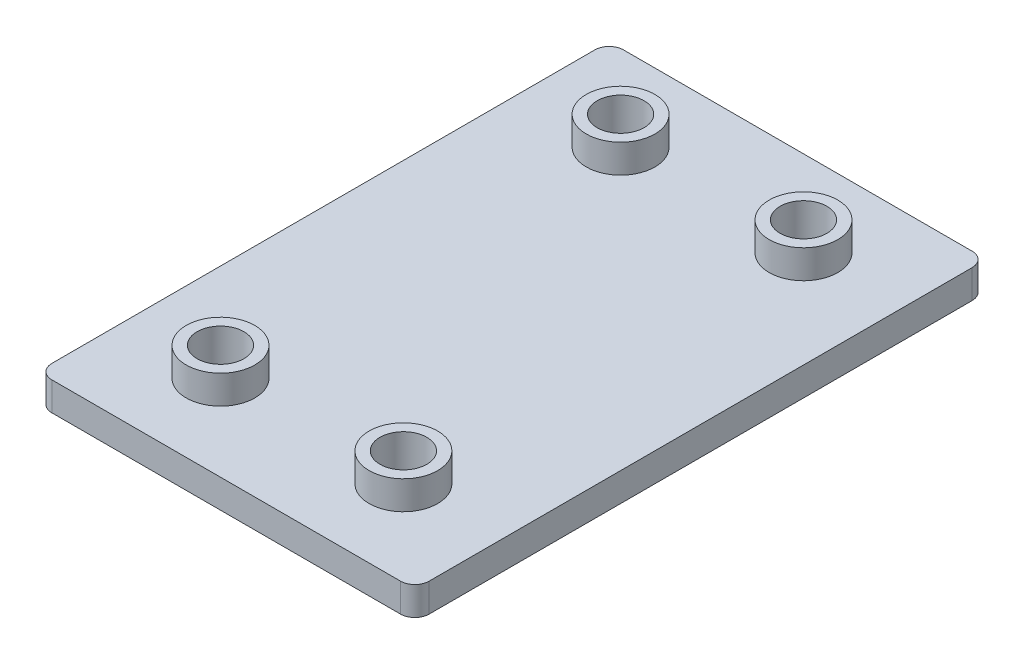
SolidWorks part; units mm, degrees
material "Custom Plastic"
ref_plane "Front Plane" through (0, 0, 0) normal (0, 0, 1) x (1, 0, 0)
ref_plane "Top Plane" through (0, 0, 0) normal (0, 1, 0) x (1, 0, 0)
ref_plane "Right Plane" through (0, 0, 0) normal (1, 0, 0) x (0, 0, -1)
sketch "Sketch1" plane through (0, 0, 0) normal (0, 1, 0) x (1, 0, 0)
  line L0 (0, 0) -> (0, -6.9405) construction
  line L1 (33, -50) -> (-33, -50)
  line L2 (33, -50) -> (33, 50)
  line L3 (33, 50) -> (-33, 50)
  line L4 (-33, -50) -> (-33, 50)
  line L5 (33, -50) -> (-33, 50) construction
  line L6 (33, 50) -> (-33, -50) construction
  line L7 (0, 0) -> (-7.7524, 0) construction
  point P0 (0, 0)
  dimension "D1" = 66
  dimension "D2" = 100
extrude "Boss-Extrude1" add sketch "Sketch1" along normal blind 5
sketch "Sketch2" plane through (0, 5, 0) normal (0, 1, 0) x (1, 0, 0)
  line L0 (0, 0) -> (0, -50000) construction
  line L1 (0, 0) -> (50000, 0) construction
  line L2 (33, 50) -> (-33, 50) construction
  circle A0 centre (-16, 35) radius 6
  circle A2 centre (16, 35) radius 6
  circle A3 centre (16, -35) radius 6
  circle A4 centre (-16, -35) radius 6
  dimension "D3" = 12
  dimension "D1" = 15
  dimension "D2" = 16
extrude "Boss-Extrude2" add sketch "Sketch2" along normal blind 5
hole_wizard "CBORE for M5 Hex Head Bolt1" positions "Sketch3" profile "Sketch4" counterbore size "M5" standard "ANSI Metric"
sketch "Sketch3" plane through (0, 10, 0) normal (0, 1, 0) x (1, 0, 0)
  point P0 (-16, 35)
  point P3 (16, 35)
  point P6 (16, -35)
  point P9 (-16, -35)
sketch "Sketch4" plane through (-16, 10, -35) normal (1, 0, 0) x (0, 0, 1)
  line L0 (0, 0) -> (0, 9.999)
  line L1 (0, 9.999) -> (2.5, 9.999)
  line L2 (2.5, 9.999) -> (2.5, 8)
  line L3 (2.5, 8) -> (4.1, 8)
  line L4 (4.1, 8) -> (4.1, 0)
  line L5 (4.1, 0) -> (0, 0)
  line L10 (0, 9.999) -> (-2.5, 9.999) construction
  line L11 (0, -6.35) -> (0, 107.95) construction
  dimension "Hole Dia." = 5
  dimension "Hole Depth" = 9.999
  dimension "C'Bore Dia." = 8.2
  dimension "C'Bore Depth" = 8
  dimension "Drill Angle" = 180
fillet "Fillet1" radius 2.5 4 edges at (33, 2.5, 50) (-33, 2.5, 50) (-33, 2.5, -50) (33, 2.5, -50)
